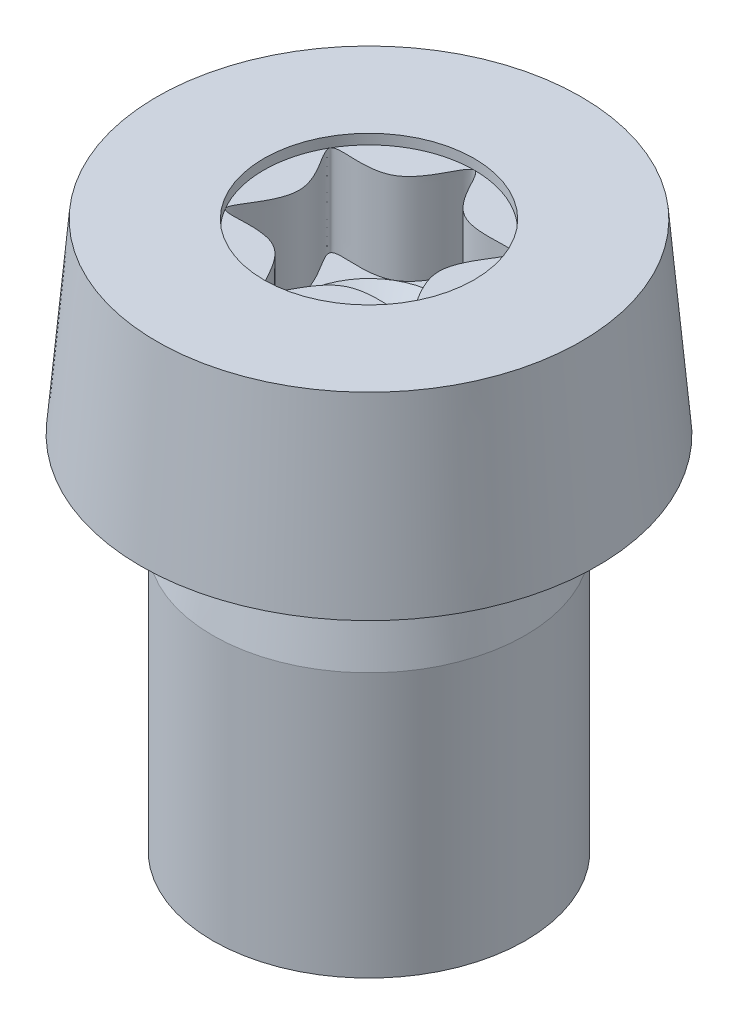
SolidWorks part; units mm, degrees
ref_plane "Front" through (0, 0, 0) normal (0, 0, 1) x (1, 0, 0)
ref_plane "Top" through (0, 0, 0) normal (0, 1, 0) x (1, 0, 0)
ref_plane "Right" through (0, 0, 0) normal (1, 0, 0) x (0, 0, -1)
sketch "Sketch1" plane through (0, 0, 0) normal (0, 0, 1) x (1, 0, 0)
  line L0 (0, 0) -> (0, 5.1006) construction
  line L1 (0, 4.55) -> (1.7644, 4.55)
  line L2 (1.7644, 4.55) -> (1.9, 3)
  line L3 (1.9, 3) -> (1.3, 3)
  line L4 (1.3, 0) -> (1.3, 2.2)
  line L5 (1.3, 0) -> (0, 0)
  line L6 (0, 0) -> (0, 4.55)
  line L7 (1.9, 3) -> (1.9, 2.6) construction
  line L8 (1.3, 2.2) -> (1.14, 3)
  line L9 (1.14, 3) -> (1.3, 3)
  line L10 (1.9, 2.6) -> (1.9, 0.6) construction
  dimension "length" = 3
  dimension "head_ht" = 1.55
  dimension "head_dia" = 3.8
  dimension "dia" = 2.6
  dimension "D1" = 5
  dimension "pitch" = 0.4
  dimension "thread_gap" = 0.8
  dimension "D2" = 0.16
  dimension "thread_length" = 2
revolve "Body-Revolve" add sketch "Sketch1" angle 360 about L0
cosmetic thread "ThreadCosmetic" [suppressed] parameters "D1"=2, "D2"=2.167
fillet "Fillet1" radius 0.1 1 edges at (0, 3, -1.14)
sketch "Sketch2" plane through (0, 4.55, 0) normal (0, 1, 0) x (-1, 0, 0)
  line L0 (0, -0.9625) -> (0, 0)
  line L1 (0, 0) -> (-0.4375, -0.7578)
  circle A0 centre (0, 0) radius 0.875
  circle A1 centre (0, 0) radius 0.5833
  spline S0 degree 3 poles (0.1887, -0.3269) (0, -1.1491) (-0.1887, -0.3269) (-0.9951, -0.5745) (-0.3774, 0) (-0.9951, 0.5745) (-0.1887, 0.3269) (0, 1.1491) (0.1887, 0.3269) (0.9951, 0.5745) (0.3774, 0) (0.9951, -0.5745) (0.1887, -0.3269) (0, -1.1491) (-0.1887, -0.3269) knots -0.25 -0.166667 -0.083333 0 0.083333 0.166667 0.25 0.333333 0.416667 0.5 0.583333 0.666667 0.75 0.833333 0.916667 1 1.083333 1.166667 1.25 only from (0, -0.875) to (0, -0.875)
  point P5 (0, -0.875)
  point P7 (-0.2917, -0.5052)
  point P10 (-0.7578, -0.4375)
  point P11 (-0.7578, 0.4375)
  point P12 (0, 0.875)
  point P13 (0.7578, 0.4375)
  point P14 (0.7578, -0.4375)
  point P15 (-0.5833, 0)
  point P16 (-0.2917, 0.5052)
  point P17 (0.2917, 0.5052)
  point P18 (0.5833, 0)
  point P19 (0.2917, -0.5052)
  dimension "socket_dia" = 1.75
  dimension "D1" = 1.1667
  dimension "D2" = 0.9625
  dimension "D3" = 30
extrude "Socket-Cut-Extrude1" cut sketch "Sketch2" against normal blind 0.84 contours S0
sketch "Sketch3" plane through (0, 4.55, 0) normal (0, 1, 0) x (-1, 0, 0)
  circle A0 centre (0, 0) radius 0.875
  dimension "D1" = 1.75
extrude "Socket-Cut-Extrude2" cut sketch "Sketch3" against normal blind 0.084
sketch "Sketch4" plane through (0, 0, 0) normal (0, 0, 1) x (1, 0, 0)
  line L0 (0, 3.71) -> (0.5833, 3.71)
  line L1 (0.761, 3.71) -> (-0.761, 3.71) construction
  line L2 (0.5833, 3.71) -> (0, 3.155)
  line L3 (0, 0) -> (0, 5.1006) construction
  line L4 (0, 3.155) -> (0, 3.71)
  line L5 (0.875, 4.55) -> (-0.875, 4.55) construction
  dimension "D1" = 1.395
  dimension "D2" = 0.5833
revolve "Drill-Cut-Revolve" cut sketch "Sketch4" angle 360 about axis through (0, 0, 0) along (0, 1, 0)
sketch "Sketch5" plane through (0, 0, 0) normal (0, 0, 1) x (1, 0, 0)
  line L0 (1.3, 0) -> (1.0835, 0.125)
  line L1 (1.0835, 0.125) -> (1.3, 0.25)
  line L2 (1.3, 0) -> (1.3, 2.2) construction
  line L3 (1.3, 0.25) -> (1.3, 0)
  line L4 (0, 0) -> (0, 5.1006) construction
  dimension "D1" = 1.0835
revolve "ThreadSchematic" [suppressed] cut sketch "Sketch5" angle 360 about axis through (0, 0, 0) along (0, 1, 0)
pattern_linear "ThdSchPat" [suppressed] count 5 spacing 0.4 along (0, 1, 0)
equation "\"D2@Sketch1\" = 0.2*\"thread_gap@Sketch1\""
equation "\"D1@Sketch2\" = \"socket_dia@Sketch2\" / 1.5"
equation "\"D2@Sketch2\" = \"socket_dia@Sketch2\" / 2 * 1.1"
equation "\"D1@Sketch3\" =\"socket_dia@Sketch2\""
equation "\"D1@Socket-Cut-Extrude2\" = .1 * \"socket_dep@Socket-Cut-Extrude1\""
equation "\"D1@Sketch4\" = 0.9*\"head_ht@Sketch1\""
equation "\"D2@Sketch4\" = \"D1@Sketch2\" / 2"
equation "\"D1@ThreadCosmetic\" = \"thread_length@Sketch1\""
equation "\"D2@ThreadCosmetic\" = \"dia@Sketch1\" - 1.0825 * \"pitch@Sketch1\""
equation "\"D1@Sketch5\" = \"D2@ThreadCosmetic\" / 2"
equation "\"D3@ThdSchPat\" = \"pitch@Sketch1\""
equation "\"D1@ThdSchPat\" = \"thread_length@Sketch1\" / \"pitch@Sketch1\""
